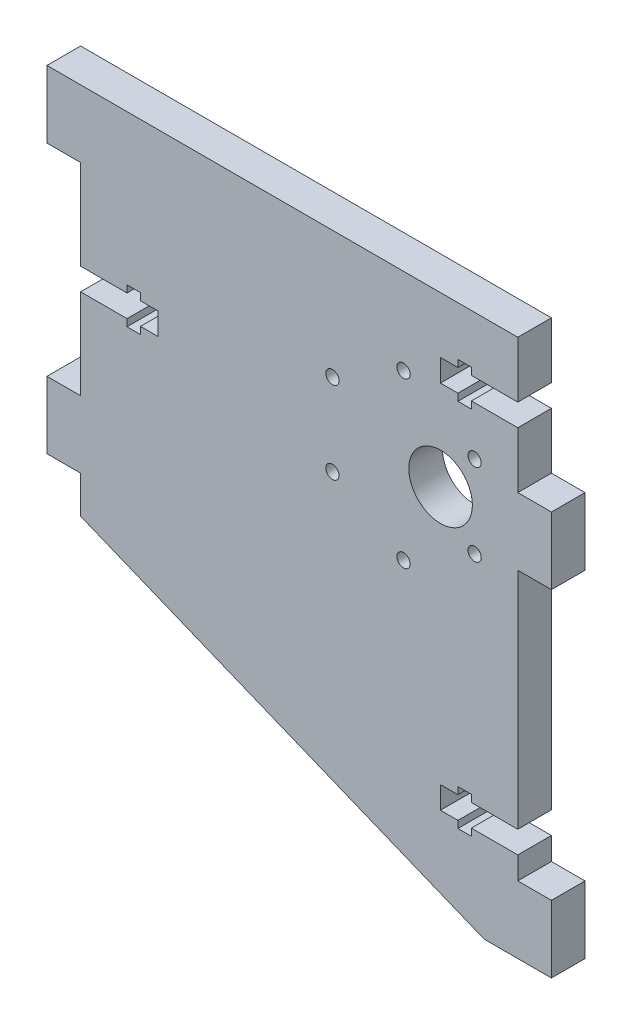
SolidWorks part; units mm, degrees
ref_plane "Front Plane" through (0, 0, 0) normal (0, 0, 1) x (1, 0, 0)
ref_plane "Top Plane" through (0, 0, 0) normal (0, 1, 0) x (1, 0, 0)
ref_plane "Right Plane" through (0, 0, 0) normal (1, 0, 0) x (0, 0, -1)
sketch "Sketch1" plane through (0, 0, 0) normal (0, 0, 1) x (1, 0, 0)
  line L0 (21.575, 33.1763) -> (21.575, -50.8) construction
  line L1 (-60.975, 31.75) -> (21.575, 31.75)
  line L2 (-60.975, 31.75) -> (-60.975, -38.7889)
  line L4 (21.575, 31.75) -> (21.575, -38.7889)
  line L5 (43.8, -38.7889) -> (-60.975, -38.7889) construction
  line L6 (-60.975, -38.7889) -> (15.225, -69.85)
  line L7 (15.225, -69.85) -> (21.575, -69.85)
  line L8 (21.575, -69.85) -> (21.575, -38.7889)
extrude "Boss-Extrude1" add sketch "Sketch1" along normal blind 6.35
sketch "Sketch2" plane through (21.575, 0, 0) normal (1, 0, 0) x (0, 0, -1)
  line L0 (0, -69.85) -> (0, 31.75) construction
  line L1 (-6.35, -69.85) -> (0, -69.85)
  line L2 (-6.35, -69.85) -> (-6.35, -57.15)
  line L3 (-6.35, -57.15) -> (0, -57.15)
  line L4 (0, -69.85) -> (0, -57.15)
  line L5 (0, -57.15) -> (-6.35, -57.15) construction
extrude "Boss-Extrude2" add sketch "Sketch2" along normal blind 6.35
pattern_linear "LPattern1" count 2 spacing 63.5 along (0, 1, 0) of "Boss-Extrude2"
sketch "Sketch3" plane through (0, 0, 0) normal (0, 0, -1) x (-1, 0, 0)
  circle A0 centre (13.4234, 7.75) radius 1.25
  circle A1 centre (13.4234, -7.75) radius 1.25
  circle A2 centre (0, 15.5) radius 1.25
  circle A3 centre (-13.4234, 7.75) radius 1.25
  circle A4 centre (-13.4234, -7.75) radius 1.25
  circle A5 centre (0, -15.5) radius 1.25
  circle A6 centre (-7, 0) radius 6
extrude "Cut-Extrude1" cut sketch "Sketch3" against normal through all
sketch "Sketch4" plane through (-60.975, 0, 0) normal (-1, 0, 0) x (0, 0, 1)
  line L0 (6.35, 31.75) -> (6.35, -38.7889) construction
  line L1 (0, 31.75) -> (6.35, 31.75)
  line L2 (0, 31.75) -> (0, 19.05)
  line L3 (0, 19.05) -> (6.35, 19.05)
  line L4 (6.35, 31.75) -> (6.35, 19.05)
  line L5 (0, 19.05) -> (6.35, 19.05) construction
  line L6 (0, 31.75) -> (0, -38.7889) construction
  line L7 (0, -19.0834) -> (6.35, -19.0834)
  line L8 (0, -19.0834) -> (0, -31.75)
  line L9 (0, -31.75) -> (6.35, -31.75)
  line L10 (6.35, -19.0834) -> (6.35, -31.75)
  line L11 (0, -31.75) -> (6.35, -31.75) construction
extrude "Boss-Extrude3" add sketch "Sketch4" along normal blind 6.35
sketch "Sketch5" plane through (0, 0, 6.35) normal (0, 0, 1) x (1, 0, 0)
  line L0 (21.575, 33.1763) -> (21.575, -50.8) construction
  line L2 (27.925, -48.7045) -> (21.575, -48.7045) construction
  line L3 (-60.975, 19.05) -> (-60.975, -19.0834) construction
  line L4 (-60.975, 2.0955) -> (-67.325, 2.0955) construction
  line L5 (21.575, 6.35) -> (21.575, 31.75) construction
  line L6 (21.575, 19.05) -> (-2.1429, 19.05) construction
  line B0 (-60.975, 2.0955) -> (-60.975, -2.0955)
  line B1 (-49.672, -2.0955) -> (-49.672, -3.429)
  line B2 (-49.672, -3.429) -> (-52.212, -3.429)
  line B3 (-52.212, -3.429) -> (-52.212, -2.0955)
  line B4 (-52.212, -2.0955) -> (-60.975, -2.0955)
  line B5 (-49.672, -2.0955) -> (-46.37, -2.0955)
  line B6 (-46.37, -2.0955) -> (-46.37, 2.0955)
  line B7 (-49.672, 2.0955) -> (-46.37, 2.0955)
  line B8 (-52.212, 2.0955) -> (-60.975, 2.0955)
  line B9 (-52.212, 3.429) -> (-52.212, 2.0955)
  line B10 (-49.672, 3.429) -> (-52.212, 3.429)
  line B11 (-49.672, 2.0955) -> (-49.672, 3.429)
  line B12 (21.575, -52.8955) -> (21.575, -48.7045)
  line B13 (10.272, -48.7045) -> (10.272, -47.371)
  line B14 (10.272, -47.371) -> (12.812, -47.371)
  line B15 (12.812, -47.371) -> (12.812, -48.7045)
  line B16 (12.812, -48.7045) -> (21.575, -48.7045)
  line B17 (10.272, -48.7045) -> (6.97, -48.7045)
  line B18 (6.97, -48.7045) -> (6.97, -52.8955)
  line B19 (10.272, -52.8955) -> (6.97, -52.8955)
  line B20 (12.812, -52.8955) -> (21.575, -52.8955)
  line B21 (12.812, -54.229) -> (12.812, -52.8955)
  line B22 (10.272, -54.229) -> (12.812, -54.229)
  line B23 (10.272, -52.8955) -> (10.272, -54.229)
  line B24 (21.575, -50.8) -> (6.97, -50.8) construction
  line B25 (21.575, 16.9545) -> (21.575, 21.1455)
  line B26 (10.272, 21.1455) -> (10.272, 22.479)
  line B27 (10.272, 22.479) -> (12.812, 22.479)
  line B28 (12.812, 22.479) -> (12.812, 21.1455)
  line B29 (12.812, 21.1455) -> (21.575, 21.1455)
  line B30 (10.272, 21.1455) -> (6.97, 21.1455)
  line B31 (6.97, 21.1455) -> (6.97, 16.9545)
  line B32 (10.272, 16.9545) -> (6.97, 16.9545)
  line B33 (12.812, 16.9545) -> (21.575, 16.9545)
  line B34 (12.812, 15.621) -> (12.812, 16.9545)
  line B35 (10.272, 15.621) -> (12.812, 15.621)
  line B36 (10.272, 16.9545) -> (10.272, 15.621)
sketch_block_instance "TSlot-1"
sketch_block "TSlot" parameters "D1"=3.302, "D2"=2.54, "D3"=3.175, "D4"=8.763, "D5"=1.3462
sketch_block_instance "TSlot-3"
sketch_block_instance "TSlot-6"
extrude "Cut-Extrude2" cut sketch "Sketch5" against normal through all
